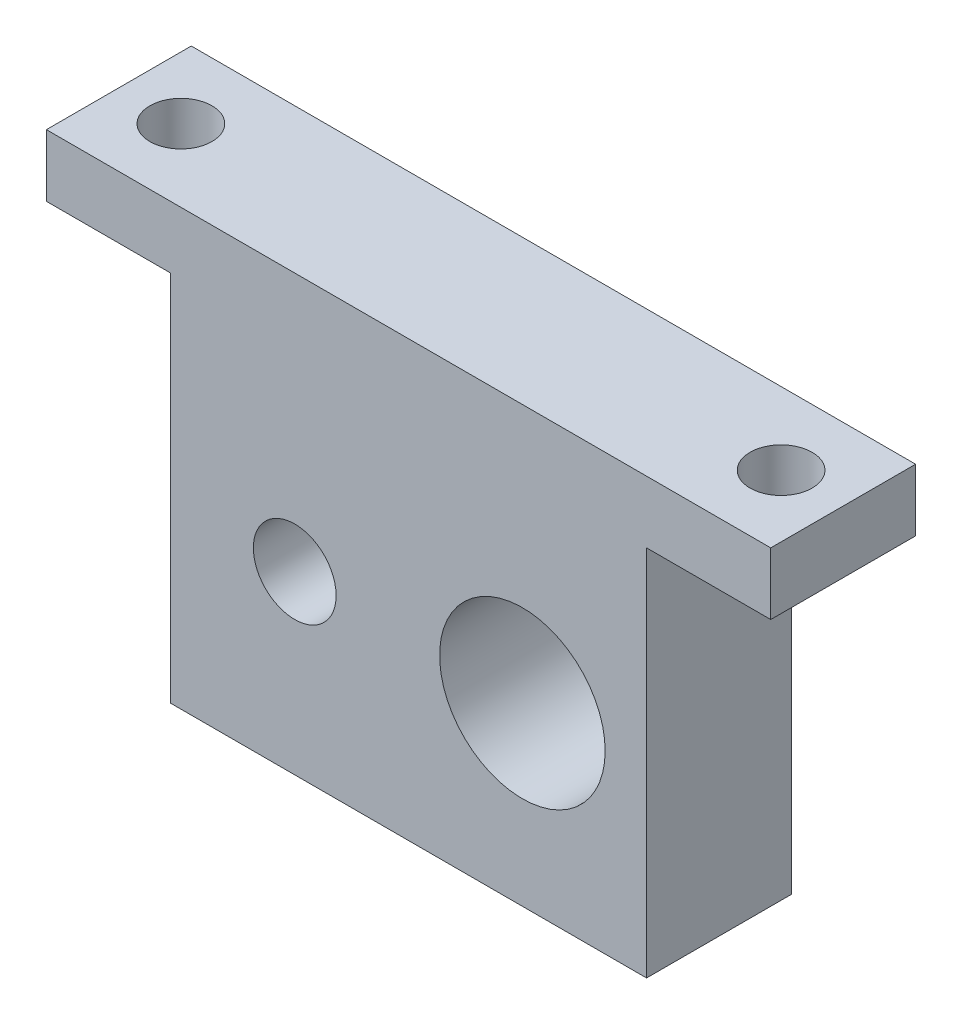
SolidWorks part; units mm, degrees
ref_plane "前视基准面" through (0, 0, 0) normal (0, 0, 1) x (1, 0, 0)
ref_plane "上视基准面" through (0, 0, 0) normal (0, 1, 0) x (1, 0, 0)
ref_plane "右视基准面" through (0, 0, 0) normal (1, 0, 0) x (0, 0, -1)
sketch "草图1" plane through (0, 0, 0) normal (0, 0, 1) x (1, 0, 0)
  line L0 (-35, 15) -> (-23, 15)
  line L1 (-35, -21) -> (35, -21)
  line L2 (-35, -21) -> (-35, 21)
  line L3 (-35, 21) -> (35, 21)
  line L4 (35, -21) -> (35, 21)
  line L5 (-35, -21) -> (35, 21) construction
  line L6 (-35, 21) -> (35, -21) construction
  line L7 (-23, 15) -> (-23, -21)
  line L8 (35, 15) -> (23, 15)
  line L9 (23, 15) -> (23, -21)
  line L10 (0, 21) -> (0, -21) construction
  circle A0 centre (-11, -4) radius 4
  circle A1 centre (11, -4) radius 8
  point P0 (0, 0)
  dimension "D6" = 8
  dimension "D7" = 22
  dimension "D9" = 16
  dimension "D10" = 25
  dimension "D11" = 11
  dimension "D1" = 70
  dimension "D2" = 42
  dimension "D3" = 12
  dimension "D4" = 12
  dimension "D5" = 6
  dimension "D8" = 25
extrude "凸台-拉伸1" add sketch "草图1" along normal blind 14 contours L9 L8 L4 L3 L2 L0 L7 L1 A1 A0
sketch "草图2" plane through (0, 15, 0) normal (0, -1, 0) x (1, 0, 0)
  line L0 (-35, 14) -> (-23, 14) construction
  line L3 (-35, 14) -> (-35, 0) construction
  line L6 (35, 14) -> (35, 0) construction
  line L9 (35, 14) -> (23, 14) construction
  circle A0 centre (-29, 7) radius 3
  circle A1 centre (29, 7) radius 3
  dimension "D1" = 6
  dimension "D2" = 6
  dimension "D5" = 6
  dimension "D3" = 7
  dimension "D4" = 6
  dimension "D6" = 7
extrude "切除-拉伸1" cut sketch "草图2" against normal blind 14
sketch "草图3" plane through (0, 0, 14) normal (0, 0, 1) x (1, 0, 0)
  line L0 (-11, -8) -> (-11, -21) construction
  line L1 (-23, -21) -> (23, -21) construction
  line L2 (11, -12) -> (11, -21) construction
  circle A0 centre (-11, -4) radius 4 construction
  circle A1 centre (11, -4) radius 8 construction
